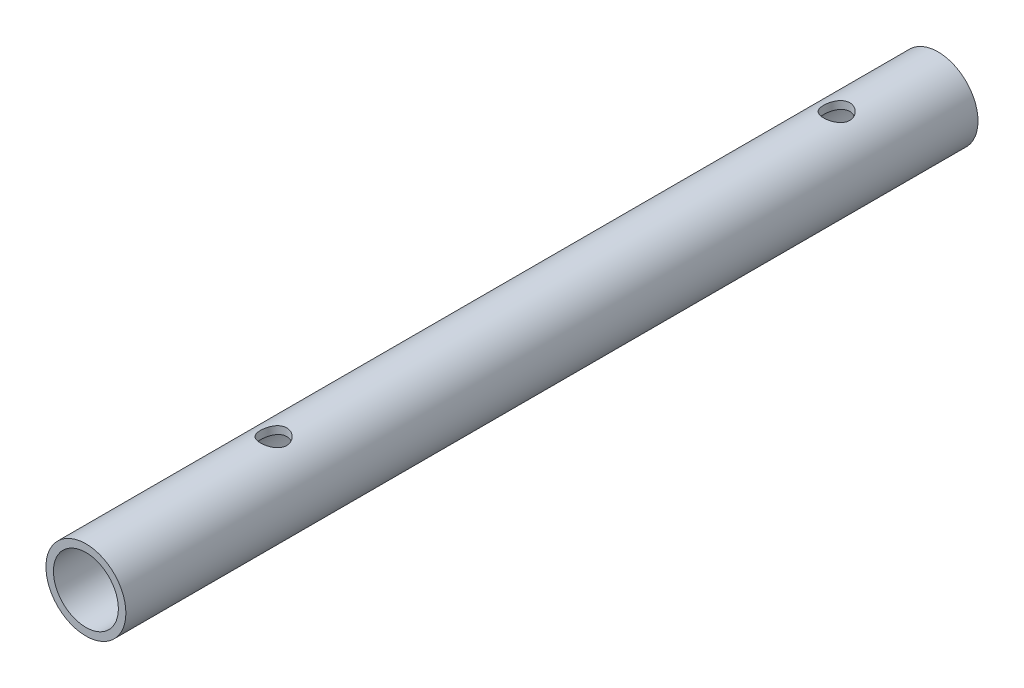
SolidWorks part; units mm, degrees
material "Galvanized Steel"
ref_plane "Front Plane" through (0, 0, 0) normal (0, 0, 1) x (1, 0, 0)
ref_plane "Top Plane" through (0, 0, 0) normal (0, 1, 0) x (1, 0, 0)
ref_plane "Right Plane" through (0, 0, 0) normal (1, 0, 0) x (0, 0, -1)
sketch "Sketch1" plane through (0, 0, 0) normal (0, 0, 1) x (1, 0, 0)
  circle A0 centre (0, 0) radius 10.65
  circle A1 centre (0, 0) radius 8.65
  dimension "D1" = 21.3
  dimension "D2" = 2
extrude "Boss-Extrude1" add sketch "Sketch1" along normal blind 227
sketch "Sketch2" plane through (0, 0, 0) normal (0, 1, 0) x (1, 0, 0)
  line L0 (-10.65, -227) -> (10.65, -227) construction
  circle A0 centre (0, -177) radius 3.5
  dimension "D1" = 7
  dimension "D2" = 50
extrude "Cut-Extrude1" cut sketch "Sketch2" against normal through all both and the other way through all
pattern_linear "LPattern1" count 2 spacing 150 along (0, 0, -1) of "Cut-Extrude1"
sketch "Sketch3" plane through (0, 0, 0) normal (0, 1, 0) x (1, 0, 0)
  line L0 (0, -227) -> (0, -221.8415)
  line L1 (-10.65, -227) -> (-9.65, -227)
  line L2 (-10.65, -227) -> (-10.65, -220)
  line L3 (-10.65, -220) -> (-9.65, -220)
  line L4 (-9.65, -227) -> (-9.65, -220)
  line L5 (-10.65, -227) -> (-9.65, -220) construction
  line L6 (-10.65, -220) -> (-9.65, -227) construction
  line L7 (-10.65, -227) -> (10.65, -227) construction
  point P4 (-10.15, -223.5)
  dimension "D1" = 7
  dimension "D2" = 1
